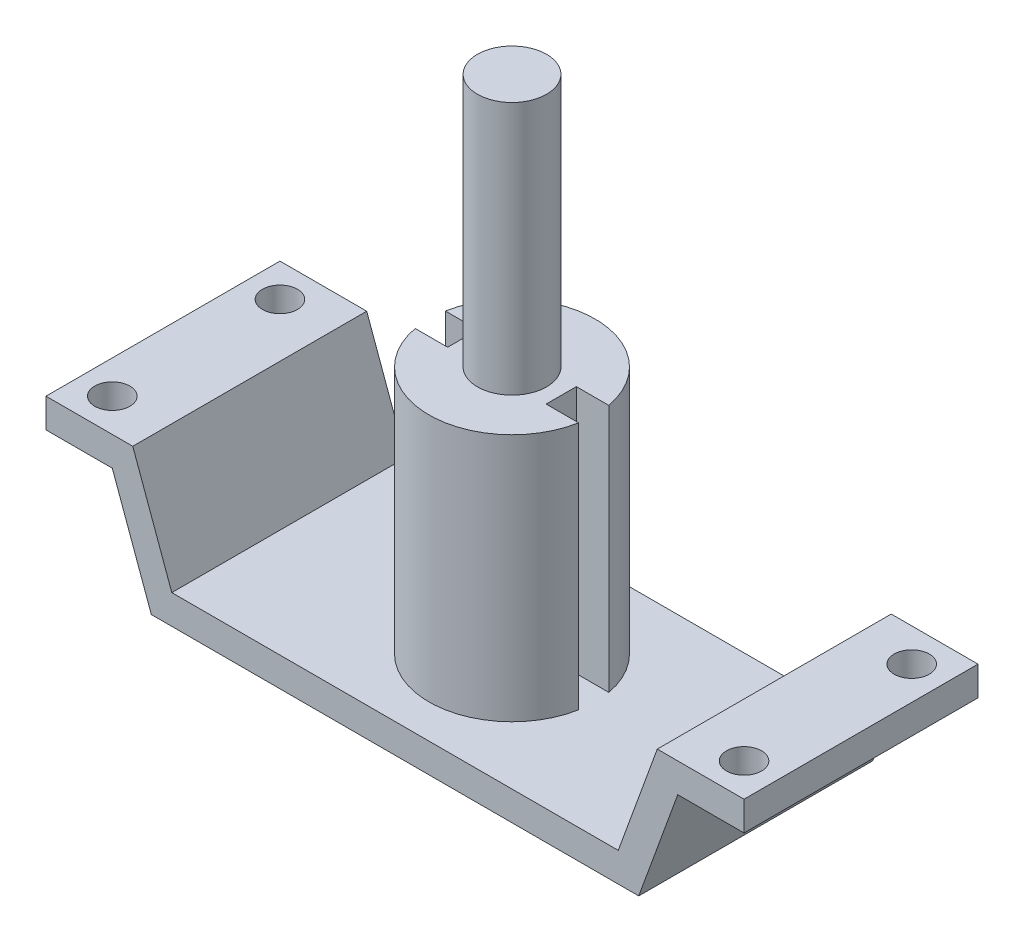
SolidWorks part; units mm, degrees
ref_plane "Front Plane" through (0, 0, 0) normal (0, 0, 1) x (1, 0, 0)
ref_plane "Top Plane" through (0, 0, 0) normal (0, 1, 0) x (1, 0, 0)
ref_plane "Right Plane" through (0, 0, 0) normal (1, 0, 0) x (0, 0, -1)
sketch "Sketch1" plane through (0, 0, 0) normal (0, 1, 0) x (1, 0, 0)
  line L1 (-25, 12) -> (25, 12)
  line L2 (-25, 12) -> (-25, -12)
  line L3 (-25, -12) -> (25, -12)
  line L4 (25, 12) -> (25, -12)
  line L5 (-25, 12) -> (25, -12) construction
  line L6 (-25, -12) -> (25, 12) construction
  point P0 (0, 0)
  dimension "D1" = 24
  dimension "D2" = 50
extrude "Boss-Extrude1" add sketch "Sketch1" along normal blind 3
sketch "Sketch2" plane through (0, 0, 12) normal (0, 0, 1) x (1, 0, 0)
  line L0 (-25, 0) -> (-29.0037, 11)
  line L1 (-29.0037, 11) -> (-35.8037, 11)
  line L2 (-35.8037, 11) -> (-35.8037, 14)
  line L3 (-35.8037, 14) -> (-26.903, 14)
  line L4 (-26.903, 14) -> (-22.8994, 3)
  line L5 (-25, 3) -> (25, 3) construction
  line L6 (-25, 0) -> (25, 0) construction
  line L7 (-25, 0) -> (-22.8994, 3)
  line L9 (0, -1.65) -> (0, 1.65) construction
  line L10 (25, 0) -> (29.0037, 11)
  line L11 (29.0037, 11) -> (35.8037, 11)
  line L12 (35.8037, 11) -> (35.8037, 14)
  line L13 (35.8037, 14) -> (26.903, 14)
  line L14 (26.903, 14) -> (22.8994, 3)
  line L15 (25, 0) -> (22.8994, 3)
  dimension "D1" = 6.8
  dimension "D2" = 3
  dimension "D3" = 3
  dimension "D4" = 11
  dimension "D5" = 70
extrude "Boss-Extrude2" add sketch "Sketch2" against normal blind 24
sketch "Sketch3" plane through (0, 3, 0) normal (0, 1, 0) x (1, 0, 0)
  circle A0 centre (0, 0) radius 8.525
  dimension "D1" = 17.05
extrude "Boss-Extrude3" add sketch "Sketch3" along normal blind 25.5
sketch "Sketch4" plane through (0, 28.5, 0) normal (0, 1, 0) x (1, 0, 0)
  circle A0 centre (0, 0) radius 3.55
  dimension "D1" = 7.1
extrude "Boss-Extrude4" add sketch "Sketch4" along normal blind 26
sketch "Sketch5" plane through (0, 28.5, 0) normal (0, 1, 0) x (1, 0, 0)
  line L0 (0, -1.65) -> (0, 1.65) construction
  line L1 (-9.05, 1.55) -> (-5.05, 1.55)
  line L2 (-9.05, 1.55) -> (-9.05, -1.55)
  line L3 (-9.05, -1.55) -> (-5.05, -1.55)
  line L4 (-5.05, 1.55) -> (-5.05, -1.55)
  line L5 (-9.05, 1.55) -> (-5.05, -1.55) construction
  line L6 (-9.05, -1.55) -> (-5.05, 1.55) construction
  line L7 (9.05, -1.55) -> (5.05, -1.55)
  line L8 (5.05, 1.55) -> (5.05, -1.55)
  line L9 (9.05, 1.55) -> (5.05, 1.55)
  line L10 (9.05, 1.55) -> (9.05, -1.55)
  point P0 (-7.05, 0)
  dimension "D1" = 3.1
  dimension "D2" = 5.05
  dimension "D3" = 4
extrude "Cut-Extrude1" cut sketch "Sketch5" against normal up to surface (25.5 mm away) up to face at (0, 3, 8.525)
sketch "Sketch6" plane through (0, 14, 0) normal (0, 1, 0) x (1, 0, 0)
  line L0 (-29.975, 0) -> (29.975, 0) construction
  line L3 (0, -13.2) -> (0, 13.2) construction
  circle A0 centre (-32.4037, 8.6) radius 1.8
  circle A1 centre (-32.4037, -8.6) radius 1.8
  circle A2 centre (32.4037, -8.6) radius 1.8
  circle A3 centre (32.4037, 8.6) radius 1.8
  dimension "D1" = 3.6
  dimension "D2" = 8.6
  dimension "D4" = 32.4037
extrude "Cut-Extrude2" cut sketch "Sketch6" against normal up to next
